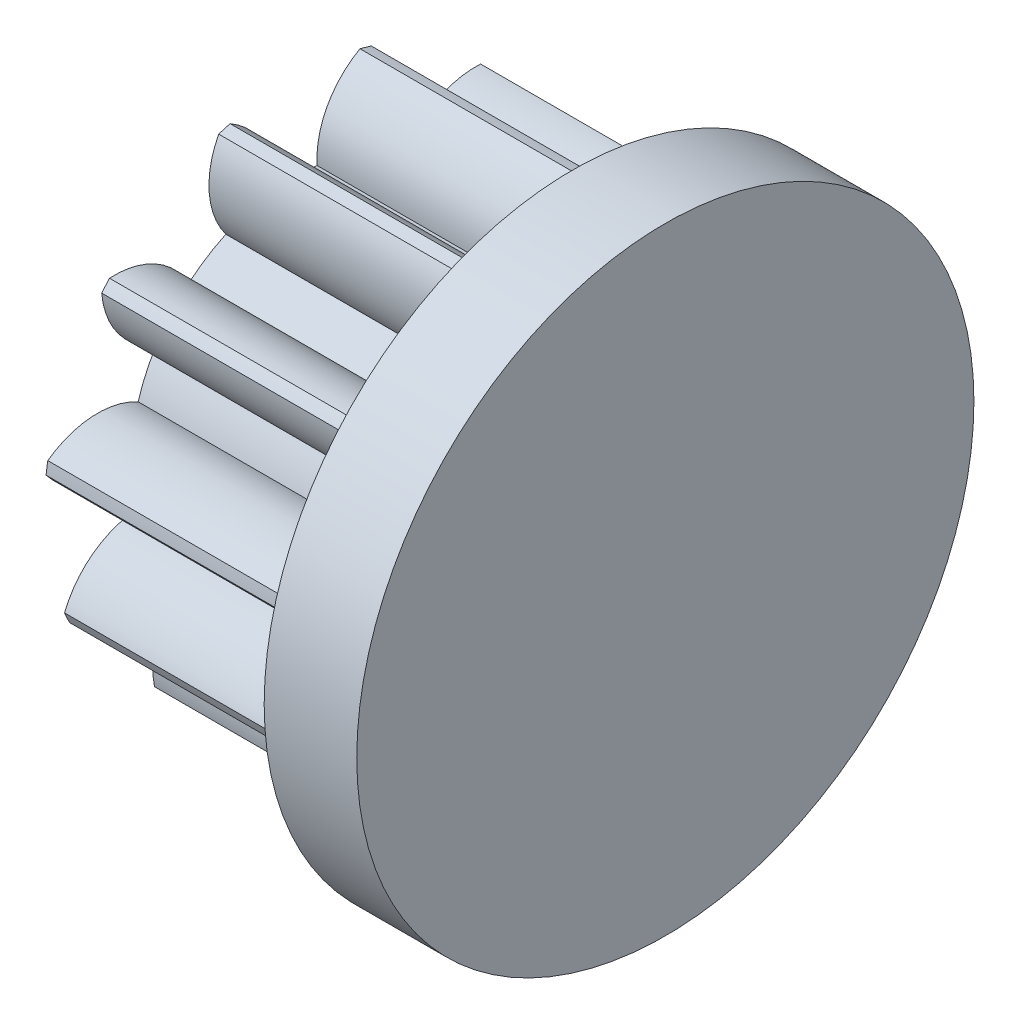
SolidWorks part; units mm, degrees
ref_plane "Plane1" through (0, 0, 0) normal (0, 0, 1) x (1, 0, 0)
ref_plane "Plane2" through (0, 0, 0) normal (0, 1, 0) x (1, 0, 0)
ref_plane "Plane3" through (0, 0, 0) normal (1, 0, 0) x (0, 0, -1)
sketch "HoldingSke" plane through (0, 0, 0) normal (0, 1, 0) x (1, 0, 0)
  line L0 (0, 0) -> (0.7853, -0.1526)
  line L1 (-15, 0) -> (100, 0) construction
  line L2 (0, 0) -> (-2.1039, 2.3779)
  line L3 (0, 0) -> (-11.863, 4.5341)
  line L4 (0, 0) -> (8.4773, 1.6478)
  line L5 (0, 0) -> (-46.8476, -17.4728)
  line L6 (0, 0) -> (-7.4607, -5.0337)
  line L7 (-2.1039, 2.3779) -> (8.6586, 51.2059)
  line L8 (-76.2, 54.61) -> (-76.1, 54.61)
  line L9 (-71.009, 38.7566) -> (-53.1078, 45.2721)
  line L10 (-76.2, 71.12) -> (104.1128, 71.12)
  line L11 (0, 0) -> (-9, 0)
  line L12 (-76.2, 101.6) -> (-76.155, 101.6)
  line L13 (24.9733, 27.94) -> (52.9518, 28.4284)
  line L14 (24.9733, 27.94) -> (24.9743, 27.94)
  line L15 (24.9733, 27.94) -> (100.4006, 29.5858)
  line L16 (-63.627, -1.25) -> (-12.827, -1.25)
  circle A0 centre (0, 0) radius 0.5
  circle A1 centre (0, 0) radius 5.3115
  circle A2 centre (0, 0) radius 37.5
  circle A3 centre (0, 0) radius 0.5
  dimension "MHD" = 10.623
  dimension "Hub_dia" = 75
  dimension "Bore" = 1
  dimension "MBD" = 1
  dimension "Num_teeth" = 11
  dimension "Pitch" = 0.8
  dimension "Overall_len" = 50
  dimension "Show_teeth" = 11
  dimension "Thickness" = 9
  dimension "OAL" = 50.0001
  dimension "T_dim" = 0.1
  dimension "Ap" = 20
  dimension "H" = 19.05
  dimension "Pitch_radius" = 180.3128
  dimension "Width" = 9
  dimension "Backlash" = 0.045
  dimension "Addendum_fac" = 1
  dimension "Dedendum_fac" = 1.25
  dimension "Clearance_fac" = 0.25
  dimension "Dedendum_add" = 0.001
  dimension "Module" = 1.25
sketch "BasProSke" plane through (0, 0, 0) normal (0, 1, 0) x (1, 0, 0)
  line L0 (-10, 0) -> (60, 0) construction
  line L1 (0, 0) -> (0, 8.125)
  line L2 (0, 0) -> (9, 0)
  line L3 (9, 0) -> (9, 8.125)
  line L4 (9, 8.125) -> (0, 8.125)
  dimension "Thickness" = 9
  dimension "Diameter" = 16.25
revolve "Base-Revolve" add sketch "BasProSke" angle 360 about L0
sketch "TooCutSke" plane through (0, 0, 0) normal (1, 0, 0) x (0, 0, -1)
  line L1 (0, 0) -> (0, 107) construction
  line L2 (0, 0) -> (-1.057, 6.7933) construction
  line L3 (0, 0) -> (-3.8405, 13.0796) construction
  line L4 (-1.057, 6.7933) -> (-1.9203, 6.5398) construction
  arc A0 (0.7167, 5.2629) -> (-0.7167, 5.2629) centre (0, 0) ccw
  arc A1 (2.1352, 7.8657) -> (-2.1352, 7.8657) centre (0, 0) ccw
  circle A2 centre (0, 0) radius 6.875 construction
  circle A3 centre (0, 0) radius 6.4604 construction
  arc A4 (-0.7167, 5.2629) -> (-2.1352, 7.8657) centre (-3.4599, 5.4558) ccw
  arc A5 (2.1352, 7.8657) -> (0.7167, 5.2629) centre (3.4599, 5.4558) ccw
  dimension "Root_dia" = 10.623
  dimension "Overcut_dia" = 16.3008
  dimension "Pitch_dia" = 13.75
  dimension "Base_dia" = 12.9208
  dimension "Flank_rad" = 2.75
  dimension "Half_ang" = 16.364
  dimension "Half_CT" = 0.8997
extrude "ToothCut" cut sketch "TooCutSke" along normal through all
fillet "Breaks" [suppressed] radius 0.025
fillet "RootFillets" [suppressed] radius 0.3135
pattern_circular "TeethCuts" count 11 every 32.727 about axis through (-10, 0, 0) along (1, 0, 0) of "ToothCut", "RootFillets", "Breaks"
sketch "HubNeaOneSke" plane through (0, 0, 0) normal (-1, 0, 0) x (0, 0, 1)
  circle A0 centre (0, 0) radius 5.3115
  dimension "Diameter" = 10.623
extrude "HubNearOne" [suppressed] add sketch "HubNeaOneSke" along normal blind 41.0001
sketch "HubNeaBotSke" plane through (0, 0, 0) normal (-1, 0, 0) x (0, 0, 1)
  circle A0 centre (0, 0) radius 5.3115
  dimension "Diameter" = 10.623
extrude "HubNearBoth" [suppressed] add sketch "HubNeaBotSke" along normal blind 20.5
ref_plane "FarPln" through (9, 0, 0) normal (1, 0, 0) x (0, 0, -1)
sketch "HubFarSke" plane through (9, 0, 0) normal (1, 0, 0) x (0, 0, -1)
  circle A0 centre (0, 0) radius 5.3115
  dimension "Diameter" = 10.623
extrude "HubFar" [suppressed] add sketch "HubFarSke" along normal blind 20.5
sketch "BorSke" plane through (0, 0, 0) normal (1, 0, 0) x (0, 0, -1)
  circle A0 centre (0, 0) radius 0.5
  dimension "Diameter" = 1
extrude "Bore" cut sketch "BorSke" along normal mid plane 100.0001
sketch "KeySke" plane through (0, 0, 0) normal (1, 0, 0) x (0, 0, -1)
  line L0 (-0.05, 0) -> (-0.05, 0.6)
  line L1 (-0.05, 0.6) -> (0.05, 0.6)
  line L2 (0.05, 0.6) -> (0.05, 0)
  line L3 (0, 0) -> (0, 34) construction
  line L4 (-0.05, 0) -> (0.05, 0)
  dimension "Offset" = 0.6
  dimension "Width" = 0.1
extrude "Keyway" [suppressed] cut sketch "KeySke" along normal mid plane 100.0001
pattern_circular "Keyway2" [suppressed] count 2 every 90 about axis through (-10, 0, 0) along (1, 0, 0)
sketch "Sketch1" plane through (9, 0, 0) normal (1, 0, 0) x (0, 0, -1)
  circle A0 centre (0, 0) radius 10
extrude "Boss-Extrude1" add sketch "Sketch1" along normal blind 3
equation "' \"Module@HoldingSke\" = 6.35"
equation "' \"Num_teeth@HoldingSke\" = 12"
equation "' \"Ap@HoldingSke\" =  20"
equation "' \"Ap@HoldingSke\" = 20"
equation "' \"Width@HoldingSke\" = 0.5 * 25.4"
equation "' \"Hub_dia@HoldingSke\"= 1 * 25.4"
equation "' \"Hub_dia@HoldingSke\" = 1 * 25.4"
equation "' \"Overall_len@HoldingSke\" = 1.0 * 25.4"
equation "' \"Bore@HoldingSke\" = 0.75 * 25.4"
equation "' \"T_dim@HoldingSke\" = 0.1 * 25.4"
equation "' \"Width@KeySke\" = 0.25 * 25.4"
equation "' \"Show_teeth@HoldingSke\" = 13"
equation "' \"Backlash@HoldingSke\" = 0.009 * 25.4"
equation "' \"Addendum_fac@HoldingSke\" = 1.0"
equation "' \"Dedendum_fac@HoldingSke\" = 1.25"
equation "' \"Dedendum_add@HoldingSke\" = 0.00005 * 25.4"
equation "' \"Clearance_fac@HoldingSke\" = 0.25"
equation "\"Pitch@HoldingSke\" = 1 / \"Module@HoldingSke\""
equation "\"Overcut_dia@TooCutSke\" = (\"Num_teeth@HoldingSke\" + 2 * \"Addendum_fac@HoldingSke\") / \"Pitch@HoldingSke\" + 0.002 * 25.4"
equation "\"Pitch_dia@TooCutSke\" = \"Num_teeth@HoldingSke\" / \"Pitch@HoldingSke\""
equation "\"Base_dia@TooCutSke\" = \"Num_teeth@HoldingSke\" / \"Pitch@HoldingSke\" * cos((\"Ap@HoldingSke\"  * 3.14159265 / 180))"
equation "\"Root_dia@TooCutSke\" = (\"Num_teeth@HoldingSke\" + 2) / \"Pitch@HoldingSke\" - 2 * (\"Addendum_fac@HoldingSke\" + \"Dedendum_fac@HoldingSke\") / \"Pitch@HoldingSke\" - \"Dedendum_add@HoldingSke\" * 2"
equation "\"Half_ang@TooCutSke\" = 180 / \"Num_teeth@HoldingSke\""
equation "\"Half_CT@TooCutSke\" = \"Num_teeth@HoldingSke\" / \"Pitch@HoldingSke\" * sin((3.14159265 / 2 / \"Num_teeth@HoldingSke\")) / 2 - 7 * \"Backlash@HoldingSke\" / 4"
equation "\"Flank_rad@TooCutSke\" = \"Num_teeth@HoldingSke\" / \"Pitch@HoldingSke\" / 5"
equation "\"Radius@RootFillets\" = \"Clearance_fac@HoldingSke\" / \"Pitch@HoldingSke\" + \"Dedendum_add@HoldingSke\""
equation "\"Break_rad@Breaks\" = 0.02 / \"Pitch@HoldingSke\""
equation "\"Thickness@HoldingSke\" = \"Width@HoldingSke\""
equation "\"OAL@HoldingSke\" = \"Thickness@HoldingSke\""
equation "\"MHD@HoldingSke\" = (\"Num_teeth@HoldingSke\" + 2) / \"Pitch@HoldingSke\" - 2 * (\"Addendum_fac@HoldingSke\" + \"Dedendum_fac@HoldingSke\")  / \"Pitch@HoldingSke\" - \"Dedendum_add@HoldingSke\" * 2"
equation "\"MBD@HoldingSke\" = (\"Num_teeth@HoldingSke\" + 2) / \"Pitch@HoldingSke\" - 2 * (\"Addendum_fac@HoldingSke\" + \"Dedendum_fac@HoldingSke\")  / \"Pitch@HoldingSke\" - \"Dedendum_add@HoldingSke\" * 2 - 0.002 * 25.4"
equation "\"MHD@HoldingSke\" = ((sgn( \"MHD@HoldingSke\" - \"Hub_dia@HoldingSke\" )-1)*( \"MHD@HoldingSke\" - \"Hub_dia@HoldingSke\" ))/-2+ \"Hub_dia@HoldingSke\""
equation "\"MBD@HoldingSke\" = ((sgn( \"MBD@HoldingSke\" - \"Bore@HoldingSke\" )-1)*( \"MBD@HoldingSke\" - \"Bore@HoldingSke\" ))/-2+ \"Bore@HoldingSke\""
equation "\"OAL@HoldingSke\" = ((sgn( \"OAL@HoldingSke\" - \"Overall_len@HoldingSke\" )+1)*( \"OAL@HoldingSke\" - \"Overall_len@HoldingSke\" ))/2 + \"Overall_len@HoldingSke\" + 0.000002 * 25.4"
equation "\"Num_teeth@TeethCuts\" = int( \"Show_teeth@HoldingSke\" ) + 1"
equation "\"Num_teeth@TeethCuts\" = ((sgn( \"Num_teeth@TeethCuts\" - \"Num_teeth@HoldingSke\" )-1)*( \"Num_teeth@TeethCuts\" - \"Num_teeth@HoldingSke\" ))/-2+ \"Num_teeth@HoldingSke\""
equation "\"Num_teeth@TeethCuts\" = ((sgn( \"Num_teeth@TeethCuts\" - 2.0)+1)*( \"Num_teeth@TeethCuts\" - 2.0))/2 +2.0"
equation "\"Angle@TeethCuts\" = 360.0 / \"Num_teeth@HoldingSke\""
equation "\"Diameter@BasProSke\" = (\"Num_teeth@HoldingSke\" + 2 * \"Addendum_fac@HoldingSke\") / \"Pitch@HoldingSke\""
equation "\"Thickness@BasProSke\"  = \"Thickness@HoldingSke\""
equation "' \"Fillet_rad@BasProSke\" =  \"Thickness@HoldingSke\" * 0.05"
equation "' \"Fillet_rad@BasProSke\" = \"Thickness@HoldingSke\" * 0.05"
equation "\"MHD@HoldingSke\" = ((sgn( \"MHD@HoldingSke\" - \"Root_dia@TooCutSke\" )-1)*( \"MHD@HoldingSke\" - \"Root_dia@TooCutSke\" ))/-2+ \"Root_dia@TooCutSke\""
equation "\"Diameter@HubNeaOneSke\" = \"MHD@HoldingSke\""
equation "\"Length@HubNearOne\" = \"OAL@HoldingSke\" - \"Thickness@BasProSke\""
equation "\"Diameter@HubNeaBotSke\" = \"MHD@HoldingSke\""
equation "\"Length@HubNearBoth\" = ( \"OAL@HoldingSke\" - \"Thickness@BasProSke\" ) / 2.0"
equation "\"Thickness@FarPln\" = \"Thickness@BasProSke\""
equation "\"Diameter@HubFarSke\" = \"MHD@HoldingSke\""
equation "\"Length@HubFar\" = ( \"OAL@HoldingSke\" - \"Thickness@BasProSke\" ) / 2.0"
equation "\"Diameter@BorSke\" = \"MBD@HoldingSke\""
equation "\"D1@Bore\" = \"OAL@HoldingSke\" * 2.0"
equation "\"D1@Keyway\" = \"OAL@HoldingSke\" * 2.0"
equation "\"Offset@KeySke\" = \"T_dim@HoldingSke\" + \"MBD@HoldingSke\" / 2.0"
